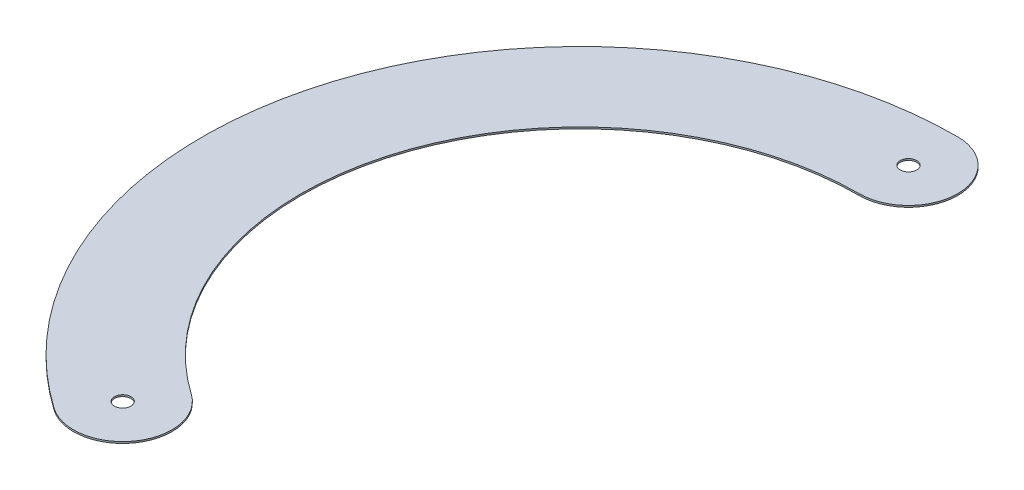
SolidWorks part; units mm, degrees
ref_plane "Front Plane" through (0, 0, 0) normal (0, 0, 1) x (1, 0, 0)
ref_plane "Top Plane" through (0, 0, 0) normal (0, 1, 0) x (1, 0, 0)
ref_plane "Right Plane" through (0, 0, 0) normal (1, 0, 0) x (0, 0, -1)
sketch "Sketch1" plane through (0, 0, 0) normal (0, 1, 0) x (1, 0, 0)
  line L0 (0, 0) -> (0, 30) construction
  line L2 (-17.2073, -24.5746) -> (0, 0) construction
  arc A0 (0, 30) -> (-17.2073, -24.5746) centre (0, 0) ccw construction
  arc A1 (0, 34.5) -> (-19.7884, -28.2607) centre (0, 0) ccw
  arc A2 (0, 25.5) -> (-14.6262, -20.8884) centre (0, 0) ccw
  arc A3 (0, 25.5) -> (0, 34.5) centre (0, 30) ccw
  arc A4 (-19.7884, -28.2607) -> (-14.6262, -20.8884) centre (-17.2073, -24.5746) ccw
  circle A5 centre (0, 30) radius 0.75
  circle A6 centre (-17.2073, -24.5746) radius 0.75
  point P4 (-28.6115, 9.0212)
  point P14 (0, 0)
  point P15 (0, 0)
  point P16 (0, 0)
  dimension "D1" = 4.5
  dimension "D2" = 1.5
  dimension "D3" = 145
  dimension "D4" = 30
extrude "Boss-Extrude1" add sketch "Sketch1" along normal blind 0.15
